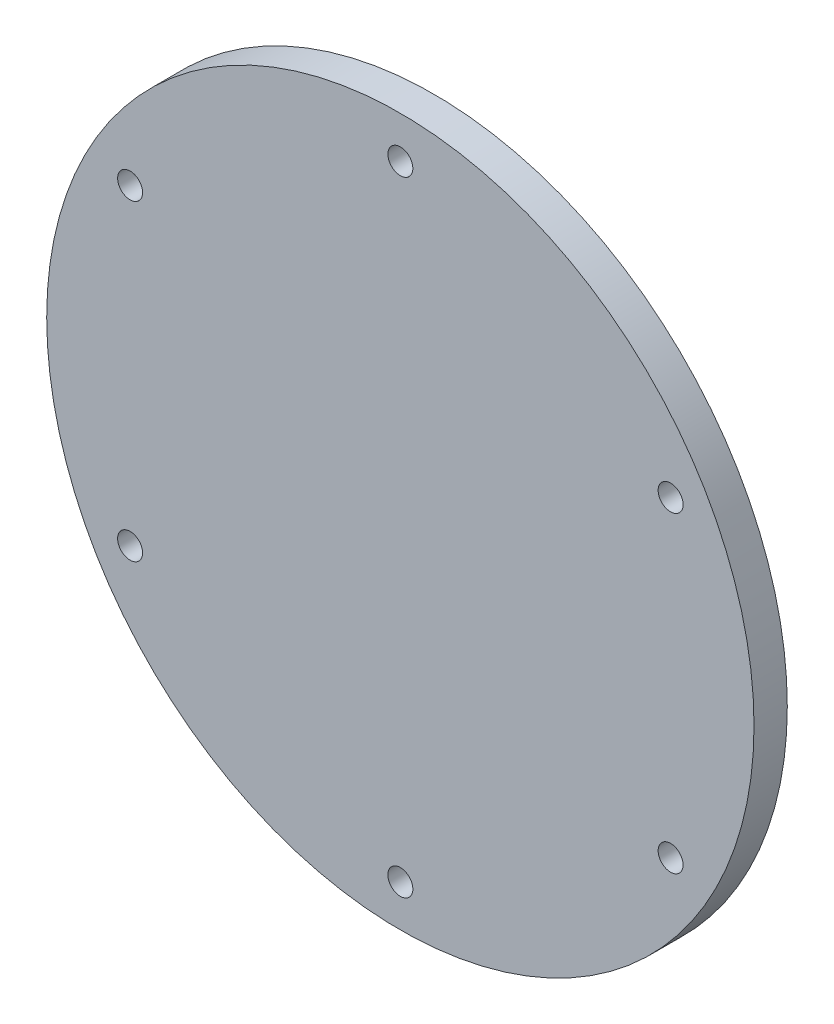
SolidWorks part; units mm, degrees
ref_plane "前视基准面" through (0, 0, 0) normal (0, 0, 1) x (1, 0, 0)
ref_plane "上视基准面" through (0, 0, 0) normal (0, 1, 0) x (1, 0, 0)
ref_plane "右视基准面" through (0, 0, 0) normal (1, 0, 0) x (0, 0, -1)
sketch "草图1" plane through (0, 0, 0) normal (0, 0, 1) x (1, 0, 0)
  circle A0 centre (0, 0) radius 85
  circle A1 centre (0, 0) radius 75 construction
  circle A2 centre (0, 75) radius 3
  circle A3 centre (64.9519, 37.5) radius 3
  circle A4 centre (64.9519, -37.5) radius 3
  circle A5 centre (0, -75) radius 3
  circle A6 centre (-64.9519, -37.5) radius 3
  circle A7 centre (-64.9519, 37.5) radius 3
  point P15 (0, 0)
  dimension "D1" = 170
  dimension "D2" = 150
  dimension "D3" = 6
  dimension "D4" = 6
extrude "凸台-拉伸1" add sketch "草图1" along normal blind 8
